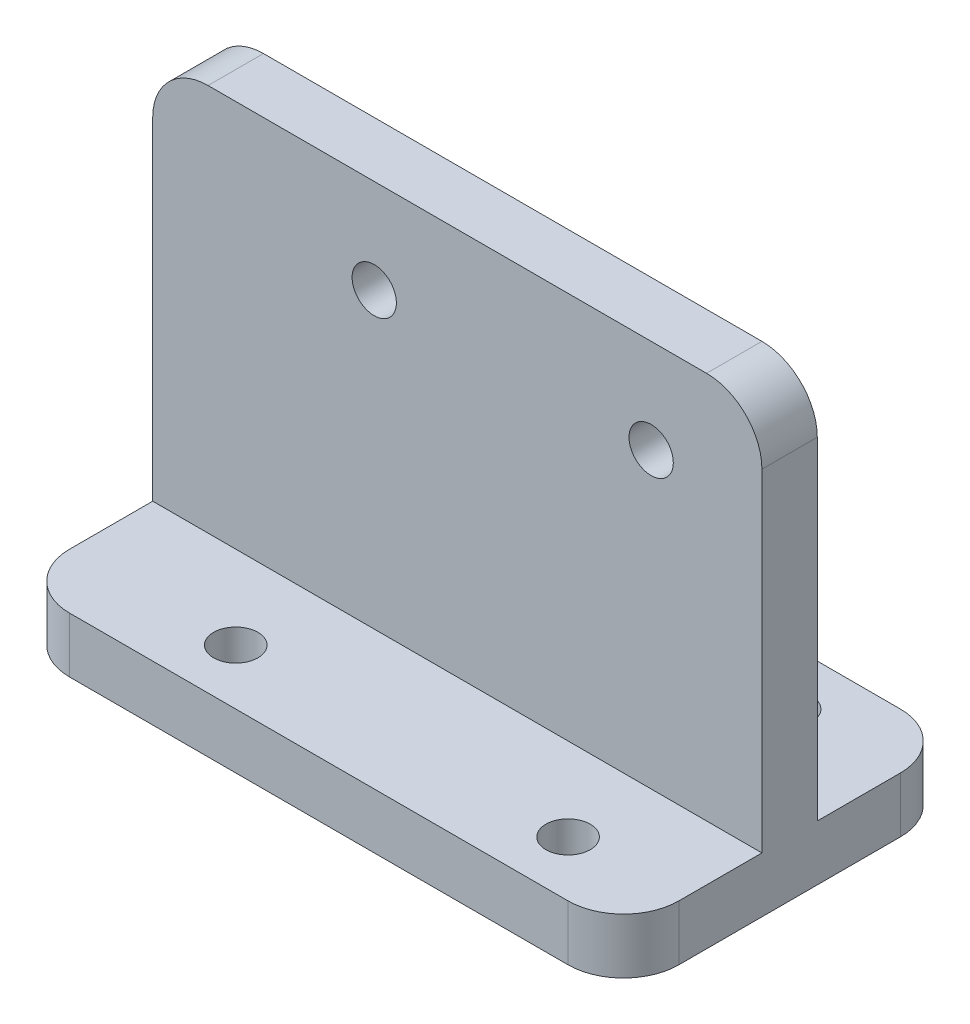
SolidWorks part; units mm, degrees
ref_plane "Front Plane" through (0, 0, 0) normal (0, 0, 1) x (1, 0, 0)
ref_plane "Top Plane" through (0, 0, 0) normal (0, 1, 0) x (1, 0, 0)
ref_plane "Right Plane" through (0, 0, 0) normal (1, 0, 0) x (0, 0, -1)
sketch "Sketch1" plane through (0, 0, 0) normal (0, 0, 1) x (1, 0, 0)
  line L1 (0, 0) -> (55, 0)
  line L2 (0, 0) -> (0, 35)
  line L3 (0, 35) -> (55, 35)
  line L4 (55, 0) -> (55, 35)
  circle A0 centre (20, 26.5) radius 2
  circle A1 centre (45, 26.5) radius 2
  dimension "D6" = 4
  dimension "D1" = 26.5
  dimension "D2" = 35
  dimension "D3" = 20
  dimension "D4" = 55
  dimension "D5" = 25
extrude "Boss-Extrude1" add sketch "Sketch1" along normal blind 5
sketch "Sketch2" plane through (0, 0, 0) normal (0, -1, 0) x (1, 0, 0)
  line L0 (0, 5) -> (55, 5) construction
  line L1 (0, -12.5) -> (55, -12.5)
  line L2 (0, -12.5) -> (0, 17.5)
  line L3 (0, 17.5) -> (55, 17.5)
  line L4 (55, -12.5) -> (55, 17.5)
  line L5 (55, 5) -> (55, 0) construction
  point P8 (55, 2.5)
  point P9 (55, 2.5)
  dimension "D1" = 30
extrude "Boss-Extrude2" add sketch "Sketch2" along normal blind 5
sketch "Sketch5" plane through (0, -5, 0) normal (0, -1, 0) x (1, 0, 0)
  line L0 (55, -12.5) -> (55, 17.5) construction
  line L1 (15, -7.5) -> (45, -7.5)
  line L2 (15, -7.5) -> (15, 12.5)
  line L3 (15, 12.5) -> (45, 12.5)
  line L4 (45, -7.5) -> (45, 12.5)
  circle A0 centre (45, 12.5) radius 2
  circle A1 centre (45, -7.5) radius 2
  circle A2 centre (15, -7.5) radius 2
  circle A3 centre (15, 12.5) radius 2
  point P10 (55, 2.5)
  point P11 (45, 2.5)
  dimension "D1" = 4
  dimension "D2" = 20
  dimension "D3" = 30
  dimension "D4" = 10
extrude "Cut-Extrude1" cut sketch "Sketch5" against normal blind 5 contours L3 A3 L2 | L2 A3 L3 | L3 A0 L4 | L4 A0 L3 | L4 A1 L1 | L1 A1 L4 | L1 A2 L2 | L2 A2 L1
fillet "Fillet1" radius 5 6 edges at (55, 35, 2.5) (55, -2.5, -12.5) (55, -2.5, 17.5) (0, -2.5, -12.5) (0, -2.5, 17.5) (0, 35, 2.5)
